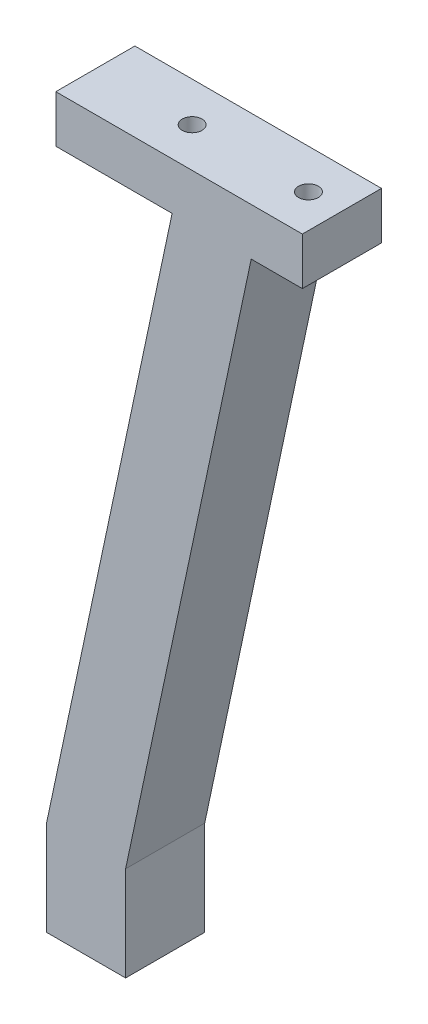
SolidWorks part; units mm, degrees
ref_plane "Front Plane" through (0, 0, 0) normal (0, 0, 1) x (1, 0, 0)
ref_plane "Top Plane" through (0, 0, 0) normal (0, 1, 0) x (1, 0, 0)
ref_plane "Right Plane" through (0, 0, 0) normal (1, 0, 0) x (0, 0, -1)
sketch "Sketch1" plane through (0, 0, 0) normal (0, 1, 0) x (1, 0, 0)
  line L1 (-10.9004, 9.3986) -> (6.0996, 9.3986)
  line L2 (-10.9004, 9.3986) -> (-10.9004, -7.6014)
  line L3 (-10.9004, -7.6014) -> (6.0996, -7.6014)
  line L4 (6.0996, 9.3986) -> (6.0996, -7.6014)
  dimension "D1" = 17
sketch "Sketch2" plane through (0, 0, 0) normal (0, 0, 1) x (1, 0, 0)
  line L0 (-10.9004, 0) -> (16.0943, 127) construction
  line L1 (-10.9004, 0) -> (6.0996, 0) construction
  line L2 (-10.9004, 0) -> (6.0996, 0) construction
  line L3 (-10.9004, 0) -> (16.0943, 127)
  dimension "D1" = 127
  dimension "D2" = 78
sweep "Sweep1" add profiles "Sketch1" path "Sketch2"
sketch "Sketch3" plane through (0, 127, 0) normal (0, 1, 0) x (1, 0, 0)
  line L0 (33.0943, 9.3986) -> (16.0943, 9.3986) construction
  line L1 (-8.9057, 9.3986) -> (44.0943, 9.3986)
  line L2 (-8.9057, 9.3986) -> (-8.9057, -7.6014)
  line L3 (-8.9057, -7.6014) -> (44.0943, -7.6014)
  line L4 (44.0943, 9.3986) -> (44.0943, -7.6014)
  line L5 (16.0943, -7.6014) -> (33.0943, -7.6014) construction
  line L6 (16.0943, 9.3986) -> (16.0943, -7.6014) construction
  dimension "D1" = 25
  dimension "D2" = 11
extrude "Boss-Extrude1" add sketch "Sketch3" along normal blind 10.16
sketch "Sketch4" plane through (0, 0, 0) normal (0, -1, 0) x (1, 0, 0)
  line L0 (-10.9004, 7.6014) -> (6.0996, 7.6014) construction
  line L1 (-5.9004, 2.6014) -> (1.0996, 2.6014)
  line L2 (-5.9004, 2.6014) -> (-5.9004, -4.3986)
  line L3 (-5.9004, -4.3986) -> (1.0996, -4.3986)
  line L4 (1.0996, 2.6014) -> (1.0996, -4.3986)
  line L5 (6.0996, 7.6014) -> (6.0996, -9.3986) construction
  line L6 (6.0996, -9.3986) -> (-10.9004, -9.3986) construction
  line L7 (-10.9004, -9.3986) -> (-10.9004, 7.6014) construction
  point P4 (-2.4004, 7.6014)
  dimension "D1" = 5
  dimension "D2" = 5
  dimension "D3" = 5
  dimension "D4" = 5
sketch "Sketch5" plane through (0, 0, 7.6014) normal (0, 0, 1) x (1, 0, 0)
  line L0 (-5.9004, 0) -> (9.9425, 74.5348)
  line L1 (-5.9004, 0) -> (1.0996, 0) construction
  line L2 (16.0943, 127) -> (-10.9004, 0) construction
  dimension "D1" = 76.2
sweep "Cut-Sweep1" cut profiles "Sketch4" path "Sketch5"
sketch "Sketch6" plane through (0, 127, 0) normal (0, -1, 0) x (1, 0, 0)
  line L0 (-8.9057, -0.8986) -> (44.0943, -0.8986) construction
  line L1 (-8.9057, -9.3986) -> (-8.9057, 7.6014) construction
  line L2 (44.0943, 7.6014) -> (44.0943, -9.3986) construction
  circle A0 centre (36.8943, -0.8986) radius 2.125
  circle A1 centre (11.8943, -0.8986) radius 2.125
  dimension "D1" = 4.25
  dimension "D2" = 25
  dimension "D3" = 7.2
extrude "Cut-Extrude1" cut sketch "Sketch6" against normal through all
sketch "Sketch7" plane through (0, 127, 0) normal (0, -1, 0) x (1, 0, 0)
  circle A0 centre (11.8943, -0.8986) radius 3.3
  circle A1 centre (36.8943, -0.8986) radius 3.3
  circle A2 centre (11.8943, -0.8986) radius 2.125 construction
  circle A4 centre (36.8943, -0.8986) radius 2.125 construction
  dimension "D1" = 6.6
extrude "Cut-Extrude2" cut sketch "Sketch7" against normal blind 3
sketch "Sketch8" plane through (-10.4292, 2.2168, 0) normal (-0.9781, 0.2079, 0) x (0, 0, 1)
  line L0 (-9.3986, 127.5709) -> (7.6014, 127.5709) construction
  line L1 (1.1014, 127.5709) -> (-2.8986, 127.5709)
  line L2 (1.1014, 127.5709) -> (1.1014, 107.5709)
  line L3 (1.1014, 107.5709) -> (-2.8986, 107.5709)
  line L4 (-2.8986, 127.5709) -> (-2.8986, 107.5709)
  line L5 (-0.8986, -2.2663) -> (-0.8986, 127.5709) construction
  line L6 (-9.3986, -2.2663) -> (7.6014, -2.2663) construction
  dimension "D1" = 20
  dimension "D2" = 4
extrude "Cut-Extrude3" cut sketch "Sketch8" against normal blind 2
sketch "Sketch9" plane through (0, 0, 0) normal (0, -1, 0) x (1, 0, 0)
  line L0 (-10.9004, 7.6014) -> (6.0996, 7.6014) construction
  line L1 (-10.9004, 7.6014) -> (6.0996, 7.6014)
  line L2 (-10.9004, 7.6014) -> (-10.9004, -9.3986)
  line L3 (-10.9004, -9.3986) -> (6.0996, -9.3986)
  line L4 (6.0996, 7.6014) -> (6.0996, -9.3986)
  line L5 (-10.9004, -9.3986) -> (-10.9004, 7.6014) construction
  line L6 (6.0996, -9.3986) -> (-10.9004, -9.3986) construction
  line L7 (6.0996, 7.6014) -> (6.0996, -9.3986) construction
extrude "Boss-Extrude2" add sketch "Sketch9" along normal blind 20.32
sketch "Sketch10" plane through (0, -20.32, 0) normal (0, -1, 0) x (1, 0, 0)
  line L0 (-10.9004, -0.8986) -> (6.0996, -0.8986) construction
  line L1 (-10.9004, 7.6014) -> (-10.9004, -9.3986) construction
  line L2 (6.0996, -9.3986) -> (6.0996, 7.6014) construction
  line L3 (-2.4004, 7.6014) -> (-2.4004, -9.3986) construction
  line L4 (6.0996, 7.6014) -> (-10.9004, 7.6014) construction
  line L5 (-10.9004, -9.3986) -> (6.0996, -9.3986) construction
  circle A0 centre (-2.4004, -0.8986) radius 1.6764
  dimension "D1" = 3.3528
extrude "Cut-Extrude4" cut sketch "Sketch10" against normal blind 15.24
